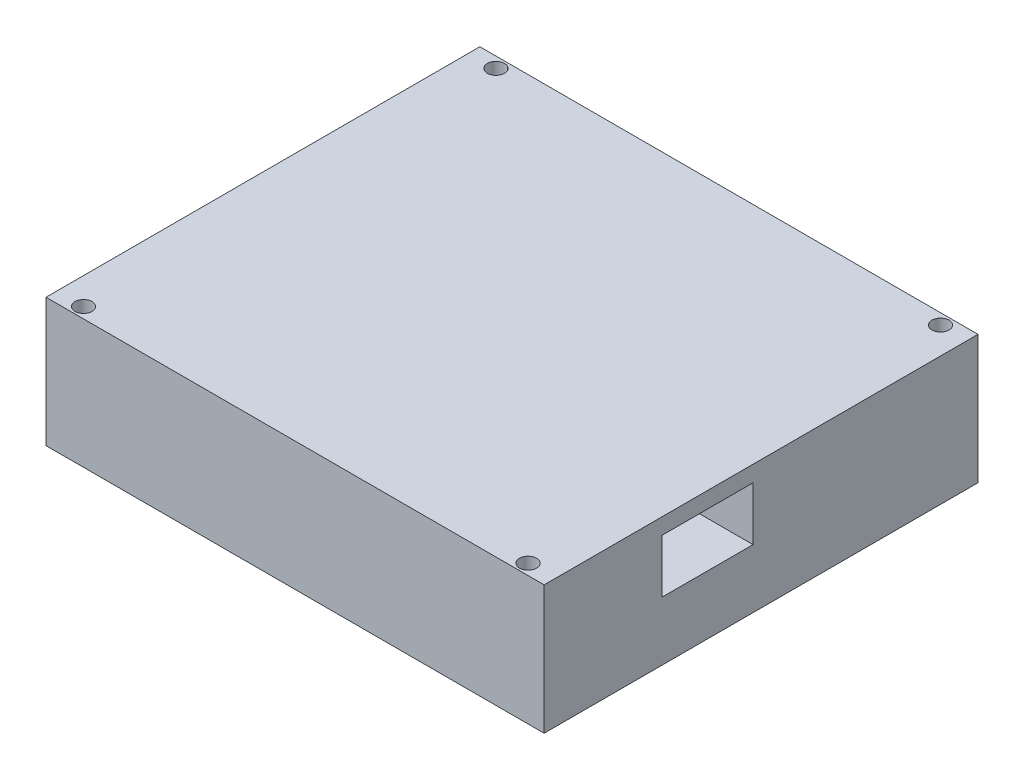
SolidWorks part; units mm, degrees
ref_plane "Front Plane" through (0, 0, 0) normal (0, 0, 1) x (1, 0, 0)
ref_plane "Top Plane" through (0, 0, 0) normal (0, 1, 0) x (1, 0, 0)
ref_plane "Right Plane" through (0, 0, 0) normal (1, 0, 0) x (0, 0, -1)
sketch "Sketch1" plane through (0, 0, 0) normal (0, 1, 0) x (1, 0, 0)
  line L1 (-46.5, 40.5) -> (46.5, 40.5)
  line L2 (-46.5, 40.5) -> (-46.5, -40.5)
  line L3 (-46.5, -40.5) -> (46.5, -40.5)
  line L4 (46.5, 40.5) -> (46.5, -40.5)
  line L5 (-46.5, 40.5) -> (46.5, -40.5) construction
  line L6 (-46.5, -40.5) -> (46.5, 40.5) construction
  point P0 (0, 0)
  dimension "D1" = 93
  dimension "D2" = 81
extrude "Boss-Extrude1" add sketch "Sketch1" along normal blind 24
sketch "Sketch2" plane through (0, 24, 0) normal (0, 1, 0) x (1, 0, 0)
  line L0 (0, 37.8168) -> (0, -38.5) construction
  line L1 (-41.5, -38.5) -> (41.5, -38.5) construction
  line L2 (-41.5, -38.5) -> (-41.5, 38.5) construction
  line L3 (-41.5, 38.5) -> (41.5, 38.5) construction
  line L4 (41.5, -38.5) -> (41.5, 38.5) construction
  line L5 (-41.5, -38.5) -> (41.5, 38.5) construction
  line L6 (-41.5, 38.5) -> (41.5, -38.5) construction
  line L7 (-41.5, 0) -> (41.5, 0) construction
  circle A0 centre (-41.5, 38.5) radius 1.6
  circle A1 centre (-41.5, -38.5) radius 1.6
  circle A2 centre (41.5, -38.5) radius 1.6
  circle A3 centre (41.5, 38.5) radius 1.6
  point P0 (0, 0)
  dimension "D3" = 3.2
  dimension "D1" = 83
  dimension "D2" = 77
extrude "Cut-Extrude1" cut sketch "Sketch2" against normal blind 24
sketch "Sketch3" plane through (46.5, 0, 0) normal (1, 0, 0) x (0, 0, -1)
  line L0 (-40.5, 24) -> (40.5, 24) construction
  line L1 (-18.5, 21) -> (-1.5, 21)
  line L2 (-18.5, 21) -> (-18.5, 11)
  line L3 (-18.5, 11) -> (-1.5, 11)
  line L4 (-1.5, 21) -> (-1.5, 11)
  line L5 (-18.5, 21) -> (-1.5, 11) construction
  line L6 (-18.5, 11) -> (-1.5, 21) construction
  line L7 (-40.5, 24) -> (-40.5, 0) construction
  point P0 (-10, 16)
  dimension "D1" = 17
  dimension "D2" = 10
  dimension "D3" = 3
  dimension "D4" = 22
extrude "Cut-Extrude2" cut sketch "Sketch3" against normal blind 20
